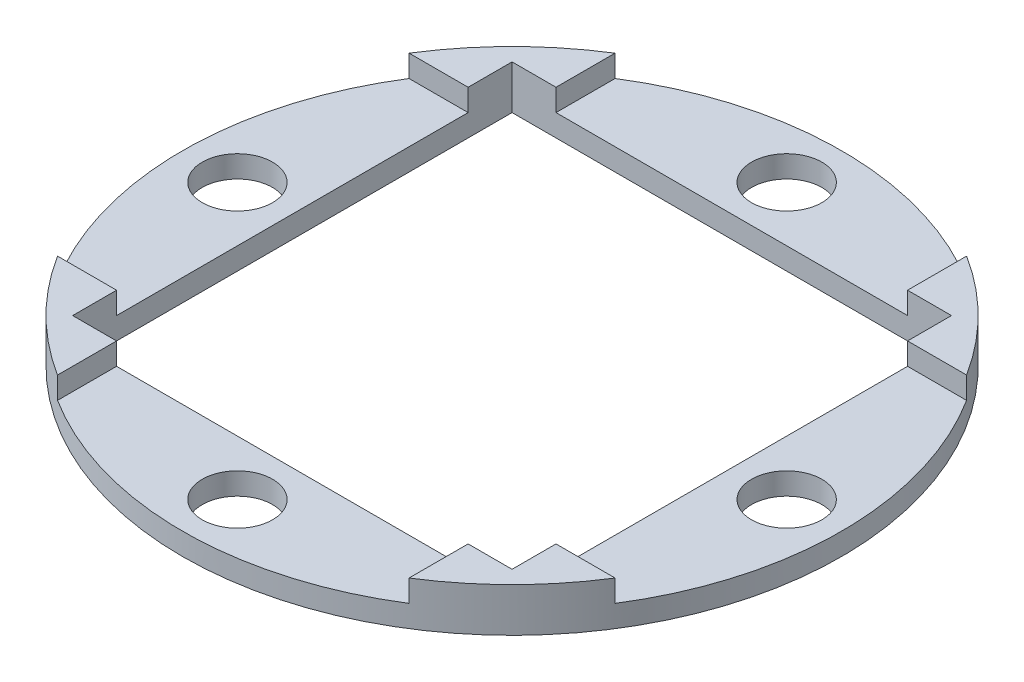
SolidWorks part; units mm, degrees
material "Custom Plastic"
ref_plane "Front Plane" through (0, 0, 0) normal (0, 0, 1) x (1, 0, 0)
ref_plane "Top Plane" through (0, 0, 0) normal (0, 1, 0) x (1, 0, 0)
ref_plane "Right Plane" through (0, 0, 0) normal (1, 0, 0) x (0, 0, -1)
sketch "Sketch1" plane through (0, 0, 0) normal (0, 1, 0) x (1, 0, 0)
  line L0 (0, 0) -> (0, -17.9724) construction
  line L1 (-50, -50) -> (50, -50)
  line L2 (-50, -50) -> (-50, 50)
  line L3 (-50, 50) -> (50, 50)
  line L4 (50, -50) -> (50, 50)
  line L5 (-50, -50) -> (50, 50) construction
  line L6 (-50, 50) -> (50, -50) construction
  line L7 (0, 0) -> (14.9739, 0) construction
  line L8 (0, 62.5) -> (14.3316, 62.5) construction
  line L9 (0, 75) -> (25.822, 75) construction
  circle A0 centre (0, 0) radius 75
  circle A1 centre (0, 0) radius 62.5 construction
  circle A2 centre (0, 62.5) radius 5
  circle A3 centre (62.5, 0) radius 5
  circle A4 centre (0, -62.5) radius 5
  circle A5 centre (-62.5, 0) radius 5
  dimension "D1" = 150
  dimension "D4" = 125
  dimension "D5" = 10
  dimension "D2" = 100
  dimension "D3" = 100
extrude "Boss-Extrude1" add sketch "Sketch1" along normal blind 5 contours A0 | L2 L1 L4 L3
sketch "Sketch2" plane through (0, 5, 0) normal (0, 1, 0) x (1, 0, 0)
  circle A0 centre (0, 0) radius 62.5 construction
  circle A1 centre (-62.5, 0) radius 8
  circle A2 centre (0, 62.5) radius 8
  circle A3 centre (62.5, 0) radius 8
  circle A4 centre (0, -62.5) radius 8
  dimension "D1" = 125
  dimension "D3" = 16
extrude "Cut-Extrude1" cut sketch "Sketch2" against normal blind 10
sketch "Sketch3" plane through (0, 5, 0) normal (0, 1, 0) x (1, 0, 0)
  line L0 (-50, -50) -> (-40, -50)
  line L3 (-40, -50) -> (-50, -50)
  line L4 (-50, -40) -> (-50, -50)
  line L5 (0, 0) -> (-85.3726, 0) construction
  line L6 (-50, 40) -> (-63.4429, 40)
  line L7 (-50, -50) -> (-50, -40)
  line L8 (-50, -40) -> (-63.4429, -40)
  line L9 (-40, -50) -> (-40, -63.4429)
  line L10 (-50, 40) -> (-50, 50)
  line L11 (-50, 50) -> (-40, 50)
  line L12 (-40, 50) -> (-40, 63.4429)
  line L13 (0, 0) -> (0, -29.0709) construction
  line L14 (50, 40) -> (50, 50)
  line L15 (50, 50) -> (40, 50)
  line L16 (40, 50) -> (40, 63.4429)
  line L17 (50, 40) -> (63.4429, 40)
  line L18 (50, -50) -> (40, -50)
  line L19 (50, -40) -> (50, -50)
  line L20 (50, -40) -> (63.4429, -40)
  line L21 (40, -50) -> (40, -63.4429)
  arc A0 (-63.4429, -40) -> (-40, -63.4429) centre (0, 0) ccw
  arc A2 (-63.4429, 40) -> (-40, 63.4429) centre (0, 0) cw
  arc A3 (63.4429, 40) -> (40, 63.4429) centre (0, 0) ccw
  arc A4 (63.4429, -40) -> (40, -63.4429) centre (0, 0) cw
  line M11 (-50, 50) -> (50, 50)
  line M12 (50, 50) -> (50, -50)
  line M13 (50, -50) -> (-50, -50)
  line M14 (-50, -50) -> (-50, 50)
  circle M15 centre (0, 0) radius 75
  dimension "D3" = 75
  dimension "D1" = 10
  dimension "D2" = 10
extrude "Boss-Extrude2" add sketch "Sketch3" along normal blind 5 contours L21 L20 M13 M15 M12 | L9 L8 M13 M14 M15 | L12 L6 M11 M15 M14 | L17 L16 M12 M15 M11
